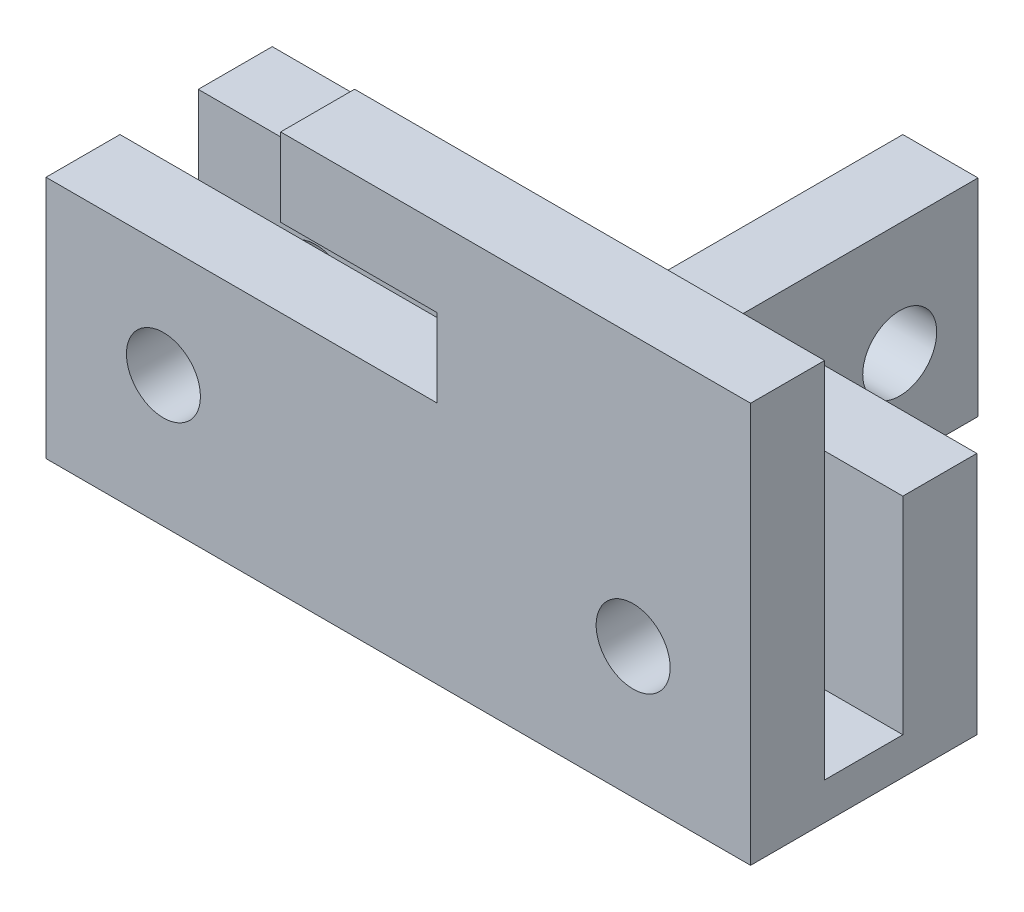
SolidWorks part; units mm, degrees
ref_plane "Front Plane" through (0, 0, 0) normal (0, 0, 1) x (1, 0, 0)
ref_plane "Top Plane" through (0, 0, 0) normal (0, 1, 0) x (1, 0, 0)
ref_plane "Right Plane" through (0, 0, 0) normal (1, 0, 0) x (0, 0, -1)
sketch "Sketch2" plane through (0, 0, 0) normal (1, 0, 0) x (0, 0, -1)
  line L0 (0, 9.882) -> (0, 0)
  line L1 (0, 0) -> (6.175, 0)
  line L2 (6.175, 0) -> (6.175, 1.5)
  line L3 (6.175, 1.5) -> (3, 1.5)
  line L4 (3, 1.5) -> (3, 9.882)
  line L5 (3, 9.882) -> (0, 9.882)
  line L7 (6.175, 0) -> (9.175, 0)
  line L8 (6.175, 0) -> (6.175, 9.882)
  line L9 (6.175, 9.882) -> (9.175, 9.882)
  line L10 (9.175, 0) -> (9.175, 9.882)
  dimension "D1" = 1.5
  dimension "D2" = 8.382
  dimension "D3" = 3
  dimension "D4" = 3.175
extrude "Boss-Extrude1" add sketch "Sketch2" along normal mid plane 28.575 contours L4 L5 L0 L1 L2 L3 | L7 L10 L9 L8 L2
sketch "Sketch4" plane through (0, 0, 0) normal (0, 0, -1) x (-1, 0, 0)
  line L0 (-9.525, 5.31) -> (9.525, 5.31) construction
  line L1 (-14.2875, 1.5) -> (14.2875, 1.5) construction
  circle A0 centre (-9.525, 5.31) radius 1.5
  circle A1 centre (9.525, 5.31) radius 1.5
  point P6 (0, 5.31)
  dimension "D1" = 3
  dimension "D2" = 3.81
  dimension "D3" = 19.05
extrude "Cut-Extrude1" cut sketch "Sketch4" along normal through all
ref_plane "Plane2" through (1.5875, 0, 0) normal (1, 0, 0) x (0, 0, -1)
sketch "Sketch8" plane through (0, 0, -9.175) normal (0, 0, -1) x (-1, 0, 0)
  line L0 (-14.2875, 9.882) -> (14.2875, 9.882) construction
  line L1 (-1.5875, 9.882) -> (1.5875, 9.882)
  line L2 (-1.5875, 9.882) -> (-1.5875, 1.5)
  line L3 (-1.5875, 1.5) -> (1.5875, 1.5)
  line L4 (1.5875, 9.882) -> (1.5875, 1.5)
  line L5 (-14.2875, 1.5) -> (14.2875, 1.5) construction
  point P6 (0, 1.5)
  dimension "D1" = 3.175
extrude "Cut-Extrude3" cut sketch "Sketch8" against normal up to next
sketch "Sketch6" plane through (1.5875, 0, 0) normal (1, 0, 0) x (0, 0, -1)
  line L0 (9.175, 0) -> (9.175, 9.882) construction
  line L1 (9.175, 9.882) -> (18.875, 9.882)
  line L2 (9.175, 9.882) -> (9.175, 1.5)
  line L3 (9.175, 1.5) -> (18.875, 1.5)
  line L4 (18.875, 9.882) -> (18.875, 1.5)
  line L5 (6.175, 1.5) -> (3, 1.5) construction
  line L6 (6.175, 1.5) -> (6.175, 9.882) construction
  circle A0 centre (15.7, 5.31) radius 1.5
  dimension "D4" = 3
  dimension "D1" = 3.81
  dimension "D2" = 9.525
  dimension "D3" = 12.7
extrude "Boss-Extrude4" add sketch "Sketch6" along normal blind 3.048
sketch "Sketch7" plane through (0, 0, -9.175) normal (0, 0, -1) x (-1, 0, 0)
  line L0 (1.5875, 9.882) -> (14.2875, 9.882) construction
  line L1 (1.8415, 9.882) -> (-1.5875, 9.882)
  line L2 (1.8415, 9.882) -> (1.8415, 1.5)
  line L3 (1.8415, 1.5) -> (-1.5875, 1.5)
  line L4 (-1.5875, 9.882) -> (-1.5875, 1.5)
  line L5 (-14.2875, 1.5) -> (-1.5875, 1.5) construction
  line L6 (-1.5875, 5.7101) -> (-1.5875, -5.7101) construction
  dimension "D1" = 3.429
extrude "Cut-Extrude2" [suppressed] cut sketch "Sketch7" against normal up to next
sketch "Sketch9" plane through (0, 0, 0) normal (0, 0, 1) x (1, 0, 0)
  line L1 (14.2875, 9.882) -> (-4.7715, 9.882)
  line L2 (14.2875, 9.882) -> (14.2875, 16.232)
  line L3 (14.2875, 16.232) -> (-4.7715, 16.232)
  line L4 (-4.7715, 9.882) -> (-4.7715, 16.232)
  line L5 (14.2875, 9.882) -> (-14.2875, 9.882) construction
  line L6 (-4.7715, 13.057) -> (1.5785, 13.057)
  line L7 (-4.7715, 13.057) -> (-4.7715, 9.882)
  line L8 (-4.7715, 9.882) -> (1.5785, 9.882)
  line L9 (1.5785, 13.057) -> (1.5785, 9.882)
  point P12 (0, 9.882)
  line M14 (14.2875, 9.882) -> (-14.2875, 9.882)
  dimension "D1" = 1.5785
  dimension "D2" = 3.175
  dimension "D3" = 6.35
  dimension "D4" = 3.175
extrude "Right Ramp Mount" add sketch "Sketch9" against normal up to surface (3 mm away) contours L6 L9 L2 L3 L4 M14 up to face at (9.525, 3.81, -3)
sketch "Sketch10" plane through (0, 0, 0) normal (0, 0, 1) x (1, 0, 0)
  line L0 (-14.2875, 9.882) -> (-14.2875, 16.232)
  line L1 (-14.2875, 16.232) -> (-1.592, 16.232)
  line L2 (-1.592, 16.232) -> (-1.592, 13.057)
  line L3 (-1.592, 13.057) -> (-7.942, 13.057)
  line L4 (-7.942, 13.057) -> (-7.942, 9.882)
  line L5 (1.5785, 9.882) -> (-14.2875, 9.882) construction
  line L6 (-14.2875, 9.882) -> (-7.942, 9.882)
  point P9 (-6.3545, 9.882)
  dimension "D1" = 1.5875
  dimension "D2" = 3.175
  dimension "D3" = 6.35
  dimension "D4" = 3.175
extrude "Left Ramp Mount" [suppressed] add sketch "Sketch10" against normal up to surface (3 mm away)
